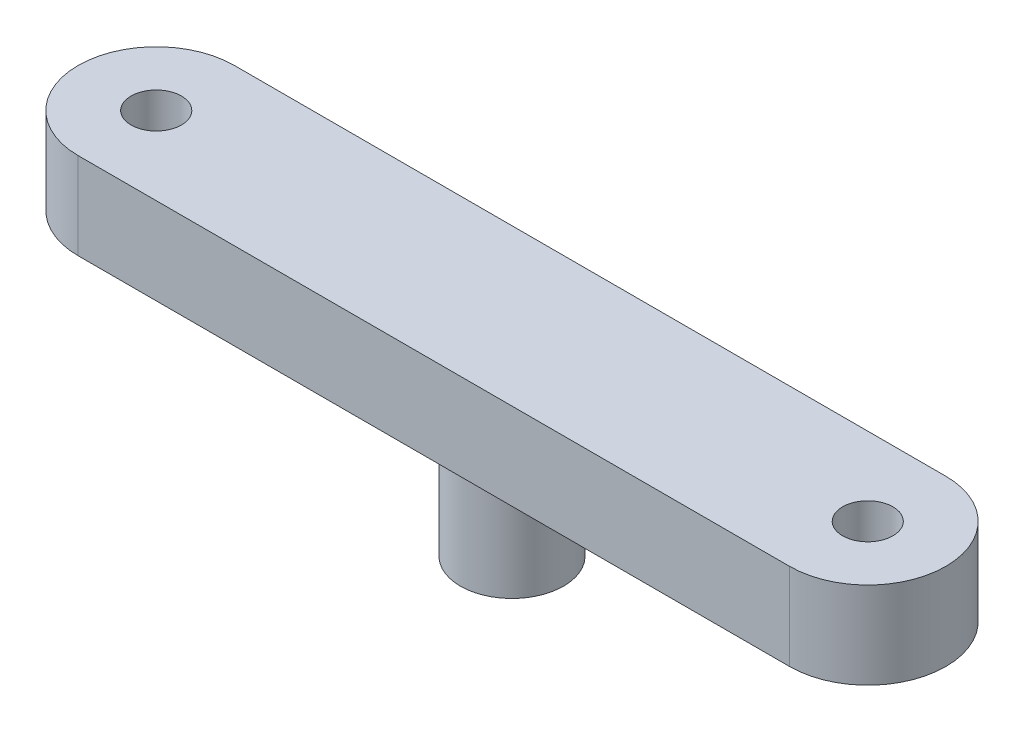
SolidWorks part; units mm, degrees
material "Aleación 6061"
ref_plane "Alzado" through (0, 0, 0) normal (0, 0, 1) x (1, 0, 0)
ref_plane "Planta" through (0, 0, 0) normal (0, 1, 0) x (1, 0, 0)
ref_plane "Vista lateral" through (0, 0, 0) normal (1, 0, 0) x (0, 0, -1)
sketch "Sk_Barra" plane through (0, 0, 0) normal (0, 1, 0) x (1, 0, 0)
  line L1 (-20.5, -494.5) -> (20.5, -494.5)
  line L2 (-20.5, -494.5) -> (-20.5, -485.5)
  line L3 (-20.5, -485.5) -> (20.5, -485.5)
  line L4 (20.5, -494.5) -> (20.5, -485.5)
  line L5 (-20.5, -494.5) -> (20.5, -485.5) construction
  line L6 (-20.5, -485.5) -> (20.5, -494.5) construction
  point P0 (0, -490)
  dimension "D1" = 41
  dimension "D2" = 9
  dimension "D3" = 490
extrude "Barra" add sketch "Sk_Barra" along normal blind 5 from offset 32.5
sketch "Sk_Extremos" plane through (0, 0, 0) normal (0, 1, 0) x (1, 0, 0)
  circle A0 centre (-20.5, -490) radius 4.5
  circle A1 centre (20.5, -490) radius 4.5
  dimension "D1" = 9
  dimension "D4" = 9
  dimension "D2" = 20.5
  dimension "D3" = 490
  dimension "D5" = 20.5
  dimension "D6" = 490
extrude "Extremos" add sketch "Sk_Extremos" along normal blind 5 from offset 32.5
sketch "Sk_Perno_696" plane through (0, 0, 0) normal (0, 1, 0) x (1, 0, 0)
  circle A0 centre (0, -490) radius 2.975
  dimension "D1" = 5.95
  dimension "D2" = 490
extrude "Perno_696" add sketch "Sk_Perno_696" along normal blind 7 from offset 39.5
sketch "Sk_Pasantes_M2-5" plane through (0, 0, 0) normal (0, 1, 0) x (1, 0, 0)
  circle A0 centre (-20.5, -490) radius 1.45
  circle A1 centre (20.5, -490) radius 1.45
  dimension "D1" = 2.9
  dimension "D4" = 2.9
  dimension "D2" = 20.5
  dimension "D3" = 490
  dimension "D5" = 20.5
  dimension "D6" = 490
extrude "Pasantes_M2-5" cut sketch "Sk_Pasantes_M2-5" along normal blind 5 from offset 32.5
sketch "Sk_Cajas_M2-5" plane through (0, 0, 0) normal (0, 1, 0) x (1, 0, 0)
  circle A0 centre (-20.5, -490) radius 2.5
  circle A1 centre (20.5, -490) radius 2.5
  dimension "D1" = 5
  dimension "D4" = 5
  dimension "D2" = 20.5
  dimension "D3" = 490
  dimension "D5" = 20.5
  dimension "D6" = 490
extrude "Cajas_M2-5" cut sketch "Sk_Cajas_M2-5" along normal blind 2.7 from offset 32.5
